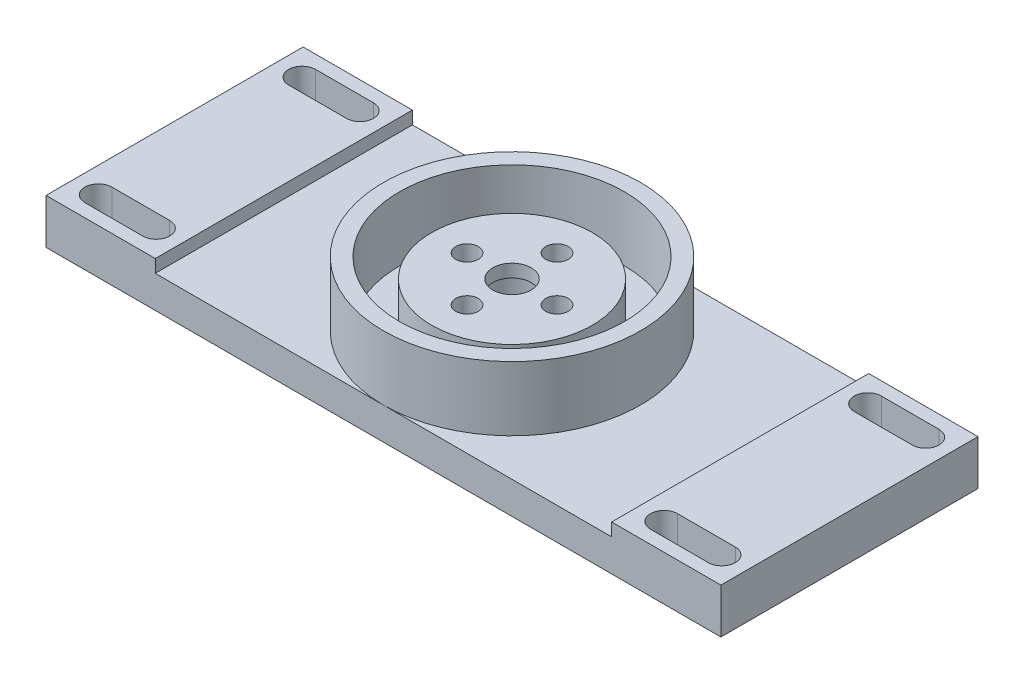
SolidWorks part; units mm, degrees
ref_plane "Front" through (0, 0, 0) normal (0, 0, 1) x (1, 0, 0)
ref_plane "Top" through (0, 0, 0) normal (0, 1, 0) x (1, 0, 0)
ref_plane "Right" through (0, 0, 0) normal (1, 0, 0) x (0, 0, -1)
sketch "Sketch1" plane through (0, 0, 0) normal (0, 1, 0) x (1, 0, 0)
  line L0 (4, 35.85) -> (13, 35.85) construction
  line L1 (0, 0) -> (105, 0)
  line L2 (0, 0) -> (0, 40)
  line L3 (0, 40) -> (105, 40)
  line L4 (105, 0) -> (105, 40)
  line L5 (4, 37.95) -> (13, 37.95)
  line L6 (4, 33.75) -> (13, 33.75)
  line L7 (4, 4.15) -> (13, 4.15) construction
  line L8 (4, 6.25) -> (13, 6.25)
  line L9 (4, 2.05) -> (13, 2.05)
  line L10 (92, 35.85) -> (101, 35.85) construction
  line L11 (92, 37.95) -> (101, 37.95)
  line L12 (92, 33.75) -> (101, 33.75)
  line L13 (92, 4.15) -> (101, 4.15) construction
  line L14 (92, 6.25) -> (101, 6.25)
  line L15 (92, 2.05) -> (101, 2.05)
  arc A0 (4, 6.25) -> (4, 2.05) centre (4, 4.15) ccw
  arc A1 (4, 37.95) -> (4, 33.75) centre (4, 35.85) ccw
  arc A2 (92, 37.95) -> (92, 33.75) centre (92, 35.85) ccw
  arc A3 (101, 33.75) -> (101, 37.95) centre (101, 35.85) ccw
  arc A4 (13, 33.75) -> (13, 37.95) centre (13, 35.85) ccw
  arc A5 (13, 2.05) -> (13, 6.25) centre (13, 4.15) ccw
  arc A6 (92, 6.25) -> (92, 2.05) centre (92, 4.15) ccw
  arc A7 (101, 2.05) -> (101, 6.25) centre (101, 4.15) ccw
  point P13 (8.5, 35.85)
  point P19 (8.5, 4.15)
  point P24 (96.5, 35.85)
  point P29 (96.5, 4.15)
  dimension "D4" = 8.5
  dimension "D6" = 4.2
  dimension "D9" = 4.15
  dimension "D10" = 4.15
  dimension "D17" = 9
  dimension "D1" = 40
  dimension "D2" = 105
  dimension "D3" = 4.15
  dimension "D5" = 8.5
  dimension "D7" = 8.5
  dimension "D8" = 4.15
  dimension "D11" = 8.5
  dimension "D12" = 9
  dimension "D13" = 9
  dimension "D14" = 9
  dimension "D15" = 4.2
  dimension "D16" = 4.2
  dimension "D18" = 4.2
extrude "Boss-Extrude1" add sketch "Sketch1" along normal blind 7
sketch "Sketch2" plane through (0, 7, 0) normal (0, 1, 0) x (1, 0, 0)
  line L1 (0, 40) -> (0, 0) construction
  line L4 (17, 0) -> (88, 0)
  line L5 (17, 0) -> (17, 40)
  line L6 (17, 40) -> (88, 40)
  line L7 (88, 0) -> (88, 40)
  line L8 (105, 0) -> (105, 40) construction
  line L9 (0, 0) -> (105, 0) construction
  dimension "D1" = 17
  dimension "D2" = 17
  dimension "D3" = 40
  dimension "D4" = 0
extrude "Cut-Extrude1" cut sketch "Sketch2" against normal blind 2
sketch "Sketch4" plane through (0, 5, 0) normal (0, 1, 0) x (1, 0, 0)
  line L0 (17, 0) -> (88, 0) construction
  line L10 (17, 40) -> (17, 0) construction
  circle A0 centre (52.5, 20) radius 20
  circle A1 centre (52.5, 20) radius 12.5
  circle A2 centre (52.5, 20) radius 17.5
  dimension "D3" = 40
  dimension "D4" = 25
  dimension "D5" = 35
  dimension "D1" = 20
  dimension "D2" = 35.5
extrude "Boss-Extrude3" add sketch "Sketch4" along normal blind 10 contours A0 A2 | A1
sketch "Sketch5" plane through (0, 15, 0) normal (0, 1, 0) x (1, 0, 0)
  circle A0 centre (52.5, 20) radius 12.5
  dimension "D1" = 25
extrude "Cut-Extrude2" cut sketch "Sketch5" against normal blind 3
sketch "Sketch6" plane through (0, 12, 0) normal (0, 1, 0) x (1, 0, 0)
  circle A0 centre (52.5, 20) radius 3
  circle A1 centre (45.5, 20) radius 1.75
  circle A2 centre (52.5, 27) radius 1.75
  circle A3 centre (59.5, 20) radius 1.75
  circle A4 centre (52.5, 13) radius 1.75
  point P14 (52.5, 20)
  dimension "D1" = 6
  dimension "D3" = 3.5
  dimension "D2" = 7
  dimension "D4" = 4
extrude "Cut-Extrude3" cut sketch "Sketch6" against normal through all
sketch "Sketch7" plane through (0, 0, 0) normal (0, -1, 0) x (1, 0, 0)
  circle A0 centre (52.5, -20) radius 4.5
  dimension "D1" = 9
extrude "Cut-Extrude4" cut sketch "Sketch7" against normal blind 10
